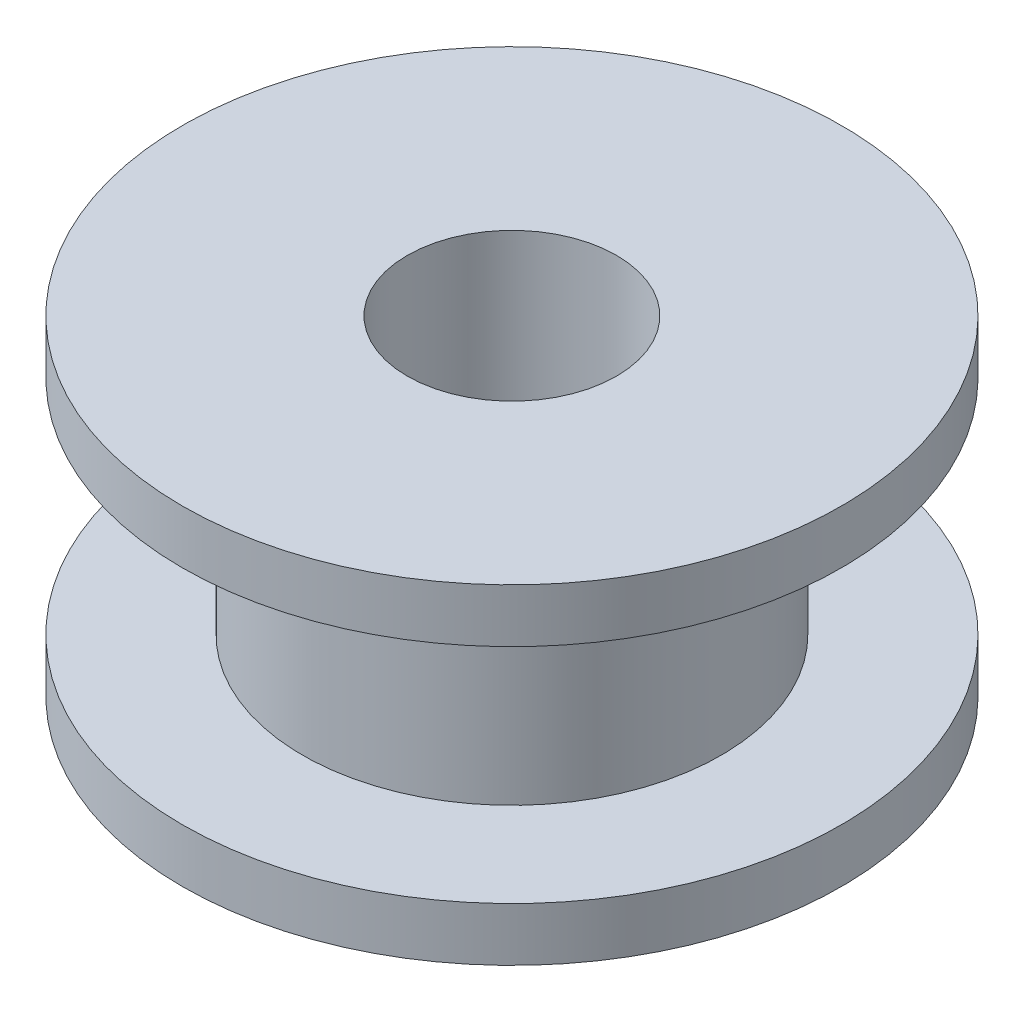
SolidWorks part; units mm, degrees
ref_plane "Front" through (0, 0, 0) normal (0, 0, 1) x (1, 0, 0)
ref_plane "Top" through (0, 0, 0) normal (0, 1, 0) x (1, 0, 0)
ref_plane "Right" through (0, 0, 0) normal (1, 0, 0) x (0, 0, -1)
sketch "Sketch1" plane through (0, 0, 0) normal (0, 1, 0) x (1, 0, 0)
  circle A0 centre (0, 0) radius 8
  circle A1 centre (0, 0) radius 2.54
  dimension "D1" = 16
  dimension "D2" = 5.08
extrude "Boss-Extrude1" add sketch "Sketch1" along normal blind 8
ref_plane "Plane1" through (0, 1.3, 0) normal (0, 1, 0) x (1, 0, 0)
sketch "Sketch2" plane through (0, 1.3, 0) normal (0, 1, 0) x (1, 0, 0)
  circle A0 centre (0, 0) radius 5.08
  circle A1 centre (0, 0) radius 8
  circle A2 centre (0, 0) radius 8
  circle A3 centre (0, 0) radius 2.54 construction
  dimension "D2" = 2.54
  dimension "D1" = 0
extrude "Cut-Extrude1" cut sketch "Sketch2" along normal blind 5.4
